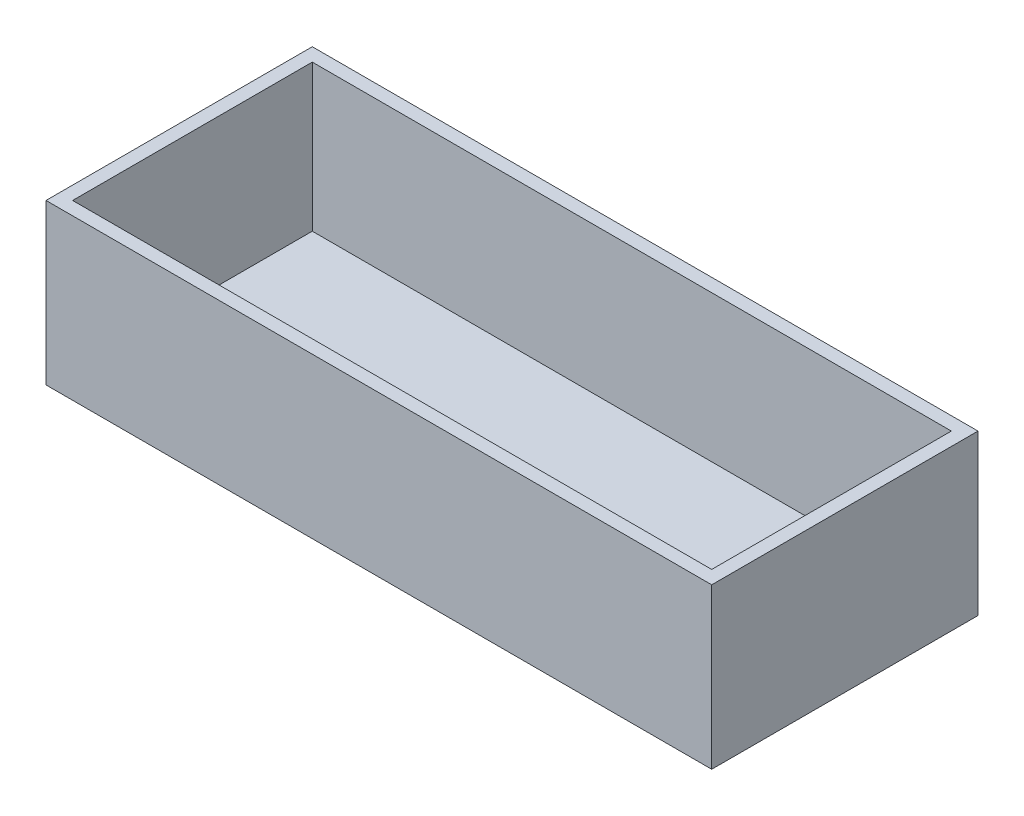
SolidWorks part; units mm, degrees
ref_plane "前视基准面" through (0, 0, 0) normal (0, 0, 1) x (1, 0, 0)
ref_plane "上视基准面" through (0, 0, 0) normal (0, 1, 0) x (1, 0, 0)
ref_plane "右视基准面" through (0, 0, 0) normal (1, 0, 0) x (0, 0, -1)
sketch "草图1" plane through (0, 0, 0) normal (0, 0, 1) x (1, 0, 0)
  line L1 (-125, -30) -> (125, -30)
  line L2 (-125, -30) -> (-125, 30)
  line L3 (-125, 30) -> (125, 30)
  line L4 (125, -30) -> (125, 30)
  line L5 (-125, -30) -> (125, 30) construction
  line L6 (-125, 30) -> (125, -30) construction
  point P0 (0, 0)
  dimension "D1" = 60
  dimension "D2" = 250
extrude "凸台-拉伸1" add sketch "草图1" along normal blind 100
shell "抽壳1" thickness 5
